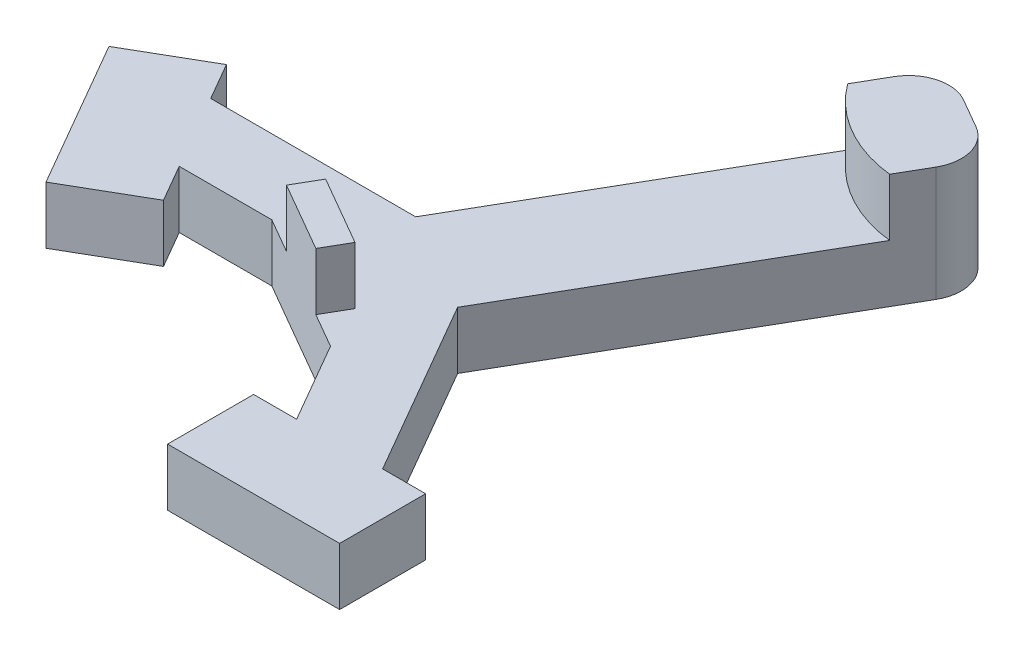
SolidWorks part; units mm, degrees
ref_plane "前视基准面" through (0, 0, 0) normal (0, 0, 1) x (1, 0, 0)
ref_plane "上视基准面" through (0, 0, 0) normal (0, 1, 0) x (1, 0, 0)
ref_plane "右视基准面" through (0, 0, 0) normal (1, 0, 0) x (0, 0, -1)
sketch "草图1" plane through (0, 0, 0) normal (0, 1, 0) x (1, 0, 0)
  line L0 (75, 20) -> (75, 35)
  line L1 (4.0609, 62.9663) -> (36.3536, 62.9663)
  line L3 (75, 35) -> (45, 35)
  line L4 (45, 35) -> (45, 20)
  line L5 (45, 20) -> (75, 20)
  line L6 (-20.1795, 74.9519) -> (-5.1795, 48.9711)
  line L9 (-5.1795, 48.9711) -> (7.8109, 56.4711)
  line L10 (7.8109, 56.4711) -> (-7.1891, 82.4519)
  line L11 (-7.1891, 82.4519) -> (-20.1795, 74.9519)
  line L12 (0, 0) -> (75, 129.9038) construction
  line L14 (0.3109, 69.4615) -> (60, 35) construction
  line L15 (60, 35) -> (60, 103.923) construction
  line L16 (60, 103.923) -> (0.3109, 69.4615) construction
  line L17 (0.3109, 69.4615) -> (40.1036, 69.4615) construction
  line L18 (40.1036, 69.4615) -> (60, 35) construction
  line L19 (36.3536, 62.9663) -> (52.5, 35)
  line L20 (-3.4391, 75.9567) -> (43.8536, 75.9567)
  line L21 (43.8536, 75.9567) -> (67.5, 35)
  line L22 (32.3066, 75.9567) -> (66.3397, 134.9038)
  line L23 (66.3397, 134.9038) -> (83.6603, 124.9038)
  line L24 (83.6603, 124.9038) -> (49.6271, 65.9567)
  line L25 (58.8397, 121.9134) -> (76.1603, 111.9134)
  dimension "D1" = 15
  dimension "D2" = 30
  dimension "D3" = 15
  dimension "D4" = 30
  dimension "D5" = 150
  dimension "D7" = 60
  dimension "D8" = 7.5
  dimension "D9" = 7.5
  dimension "D10" = 60
  dimension "D11" = 60
  dimension "D12" = 10
  dimension "D13" = 10
  dimension "D14" = 150
  dimension "D15" = 15
sketch "草图2" plane through (0, 0, 0) normal (0, 1, 0) x (1, 0, 0)
  line L0 (-20.1795, 74.9519) -> (-5.1795, 48.9711)
  line L1 (-5.1795, 48.9711) -> (7.8109, 56.4711)
  line L2 (7.8109, 56.4711) -> (4.0609, 62.9663)
  line L3 (4.0609, 62.9663) -> (20.2073, 62.9663)
  line L4 (44.4268, 48.9832) -> (52.5, 35)
  line L5 (52.5, 35) -> (45, 35)
  line L6 (45, 35) -> (45, 20)
  line L7 (45, 20) -> (75, 20)
  line L8 (75, 20) -> (75, 35)
  line L9 (75, 35) -> (67.5, 35)
  line L10 (67.5, 35) -> (49.6271, 65.9567)
  line L11 (49.6271, 65.9567) -> (83.6603, 124.9038)
  line L12 (83.6603, 124.9038) -> (66.3397, 134.9038)
  line L13 (66.3397, 134.9038) -> (32.3066, 75.9567)
  line L14 (32.3066, 75.9567) -> (-3.4391, 75.9567)
  line L15 (-3.4391, 75.9567) -> (-7.1891, 82.4519)
  line L16 (-7.1891, 82.4519) -> (-20.1795, 74.9519)
  line L23 (44.4268, 48.9832) -> (20.2073, 62.9663)
extrude "凸台-拉伸1" add sketch "草图2" along normal blind 10
sketch "草图3" plane through (0, 10, 0) normal (0, 1, 0) x (1, 0, 0)
  line L0 (0, 0) -> (80, 138.5641) construction
  line L1 (60, 35) -> (60, 103.923) construction
  line L2 (66.3397, 134.9038) -> (59.8833, 123.7209)
  line L3 (32.3066, 75.9567) -> (66.3397, 134.9038) construction
  line L4 (66.3397, 134.9038) -> (83.6603, 124.9038)
  line L5 (83.6603, 124.9038) -> (77.2038, 113.7209)
  line L6 (83.6603, 124.9038) -> (49.6271, 65.9567) construction
  arc A0 (59.8833, 123.7209) -> (77.2038, 113.7209) centre (80, 138.5641) ccw
  dimension "D2" = 30
  dimension "D3" = 50
  dimension "D1" = 160
extrude "凸台-拉伸2" add sketch "草图3" along normal blind 10
sketch "草图5" plane through (0, 10, 0) normal (0, 1, 0) x (1, 0, 0)
  line L1 (38.3792, 52.4748) -> (40.8792, 56.8049)
  line L3 (40.8792, 56.8049) -> (28.7549, 63.8049)
  line L5 (28.7549, 63.8049) -> (26.2549, 59.4748)
  line L7 (26.2549, 59.4748) -> (38.3792, 52.4748)
  line L8 (0, 0) -> (75, 129.9038) construction
  line L9 (20.2073, 62.9663) -> (44.4268, 48.9832) construction
  dimension "D1" = 5
  dimension "D2" = 7
  dimension "D3" = 14
extrude "凸台-拉伸4" add sketch "草图5" along normal blind 10
fillet "圆角1" radius 7 2 edges at (66.3397, 10, -134.9038) (83.6603, 10, -124.9038)
ref_plane "基准面1" through (30.1554, 0, -52.2308) normal (-0.5, 0, 0.866) x (0.866, 0, 0.5)
